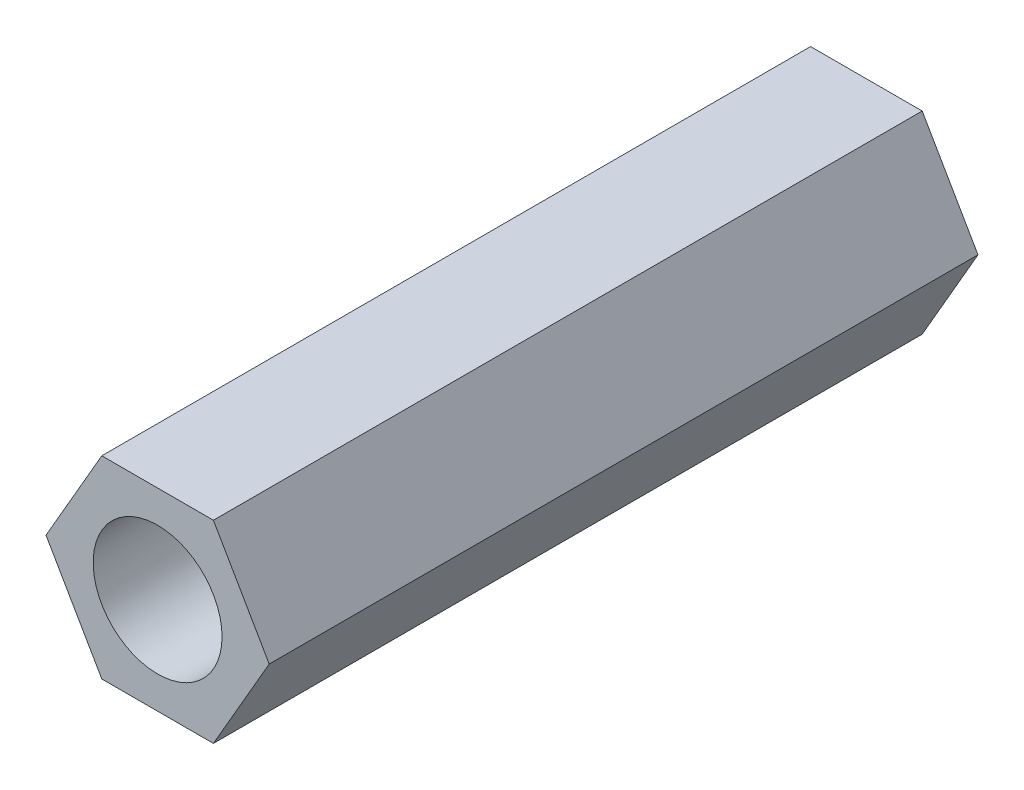
SolidWorks part; units mm, degrees
ref_plane "Plan de face" through (0, 0, 0) normal (0, 0, 1) x (1, 0, 0)
ref_plane "Plan de dessus" through (0, 0, 0) normal (0, 1, 0) x (1, 0, 0)
ref_plane "Plan de droite" through (0, 0, 0) normal (1, 0, 0) x (0, 0, -1)
sketch "Esquisse1" plane through (0, 0, 0) normal (0, 0, 1) x (1, 0, 0)
  line L1 (-3.4641, 0) -> (-1.7321, -3)
  line L2 (-1.7321, -3) -> (1.7321, -3)
  line L3 (1.7321, -3) -> (3.4641, 0)
  line L4 (3.4641, 0) -> (1.7321, 3)
  line L5 (1.7321, 3) -> (-1.7321, 3)
  line L6 (-1.7321, 3) -> (-3.4641, 0)
  circle A0 centre (0, 0) radius 2
  circle A1 centre (0, 0) radius 3 construction
  dimension "D1" = 4
  dimension "D2" = 6
extrude "Boss.-Extru.1" add sketch "Esquisse1" along normal blind 22
